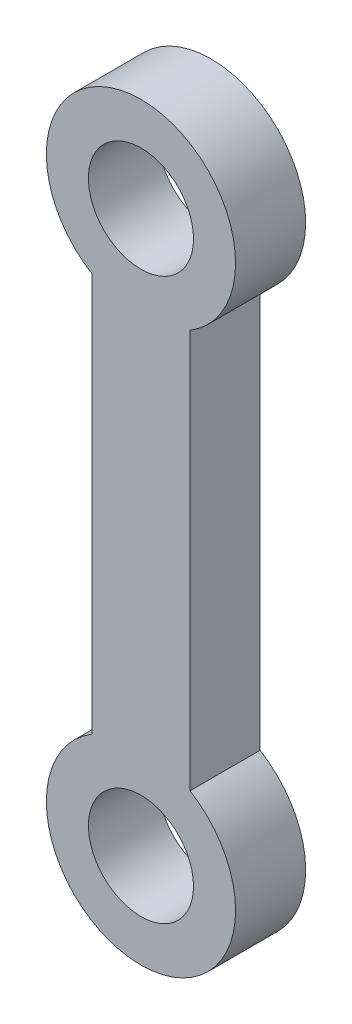
SolidWorks part; units mm, degrees
ref_plane "Front Plane" through (0, 0, 0) normal (0, 0, 1) x (1, 0, 0)
ref_plane "Top Plane" through (0, 0, 0) normal (0, 1, 0) x (1, 0, 0)
ref_plane "Right Plane" through (0, 0, 0) normal (1, 0, 0) x (0, 0, -1)
sketch "Sketch1" plane through (0, 0, 0) normal (0, 0, 1) x (1, 0, 0)
  line L0 (-2.288, 8.349) -> (-2.288, -8.7249)
  line L1 (1.912, 8.349) -> (1.912, -8.7249)
  circle A0 centre (-0.188, 11.812) radius 2.25
  arc A1 (1.912, 8.349) -> (-2.288, 8.349) centre (-0.188, 11.812) ccw
  circle A2 centre (-0.188, -12.188) radius 2.25
  arc A3 (-2.288, -8.7249) -> (1.912, -8.7249) centre (-0.188, -12.188) ccw
extrude "Boss-Extrude1" add sketch "Sketch1" along normal blind 3
